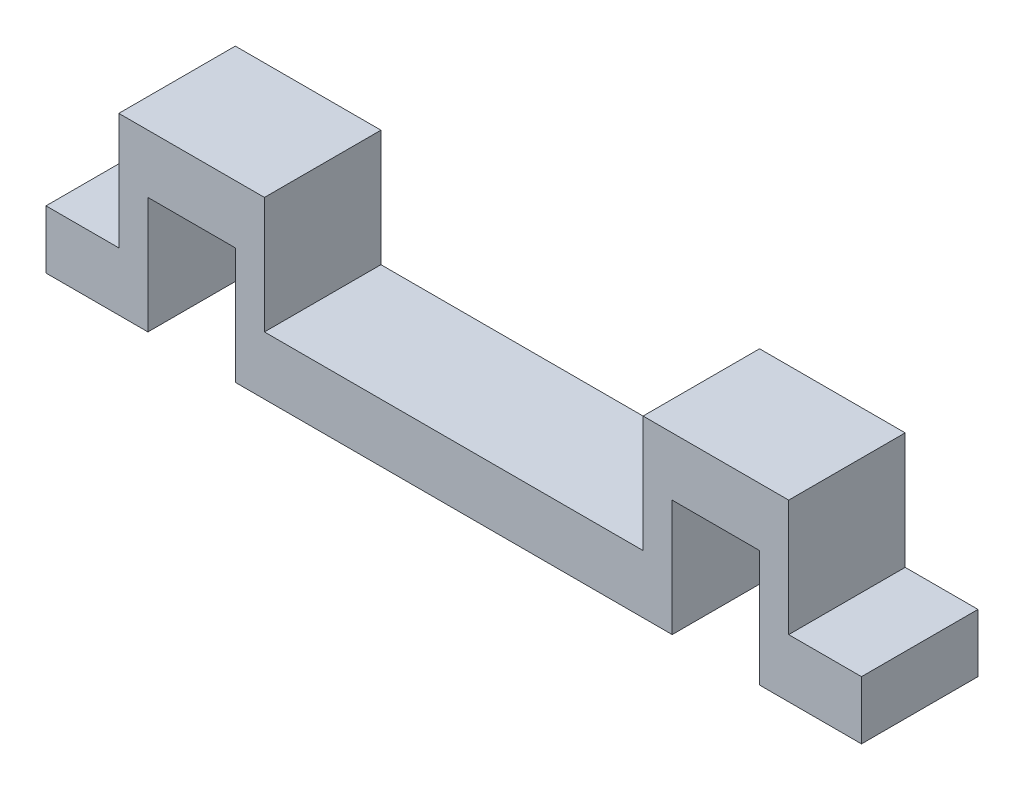
SolidWorks part; units mm, degrees
ref_plane "Front Plane" through (0, 0, 0) normal (0, 0, 1) x (1, 0, 0)
ref_plane "Top Plane" through (0, 0, 0) normal (0, 1, 0) x (1, 0, 0)
ref_plane "Right Plane" through (0, 0, 0) normal (1, 0, 0) x (0, 0, -1)
sketch "Sketch1" plane through (0, 0, 0) normal (0, 0, 1) x (1, 0, 0)
  line L0 (-37.5, 0) -> (37.5, 0)
  line L1 (-37.5, 0) -> (-37.5, 20)
  line L2 (-37.5, 20) -> (-52.5, 20)
  line L3 (-52.5, 20) -> (-52.5, 0)
  line L4 (-52.5, 0) -> (-70, 0)
  line L5 (-70, 0) -> (-70, 10)
  line L6 (-70, 10) -> (-57.5, 10)
  line L7 (-57.5, 10) -> (-57.5, 30)
  line L8 (-57.5, 30) -> (-32.5, 30)
  line L9 (-32.5, 30) -> (-32.5, 10)
  line L10 (-32.5, 10) -> (32.5, 10)
  line L12 (32.5, 30) -> (32.5, 10)
  line L13 (57.5, 30) -> (32.5, 30)
  line L14 (57.5, 10) -> (57.5, 30)
  line L15 (70, 10) -> (57.5, 10)
  line L16 (70, 0) -> (70, 10)
  line L17 (52.5, 0) -> (70, 0)
  line L18 (52.5, 20) -> (52.5, 0)
  line L19 (37.5, 20) -> (52.5, 20)
  line L20 (37.5, 0) -> (37.5, 20)
  point P0 (-70, 5)
  point P4 (0, 0)
  point P19 (0, 10)
  dimension "D1" = 5
  dimension "D2" = 17.5
  dimension "D3" = 12.5
  dimension "D4" = 15
  dimension "D5" = 20
  dimension "D6" = 25
  dimension "D7" = 20
  dimension "D8" = 20
extrude "Boss-Extrude1" add sketch "Sketch1" along normal blind 20
